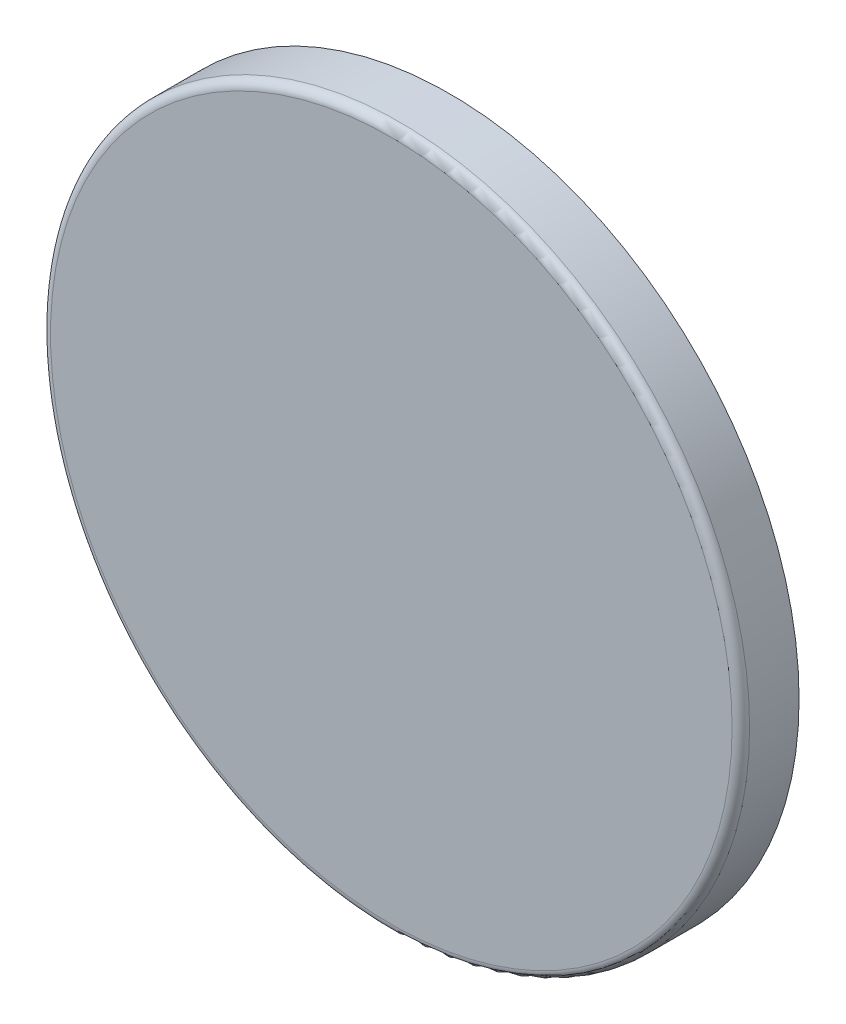
SolidWorks part; units mm, degrees
material "黄铜"
ref_plane "前视基准面" through (0, 0, 0) normal (0, 0, 1) x (1, 0, 0)
ref_plane "上视基准面" through (0, 0, 0) normal (0, 1, 0) x (1, 0, 0)
ref_plane "右视基准面" through (0, 0, 0) normal (1, 0, 0) x (0, 0, -1)
sketch "草图1" plane through (0, 0, 0) normal (0, 0, 1) x (1, 0, 0)
  circle A0 centre (0, 0) radius 6
extrude "凸台-拉伸1" add sketch "草图1" along normal blind 1
fillet "圆角1" radius 0.15 1 edges at (6, 0, 1)
